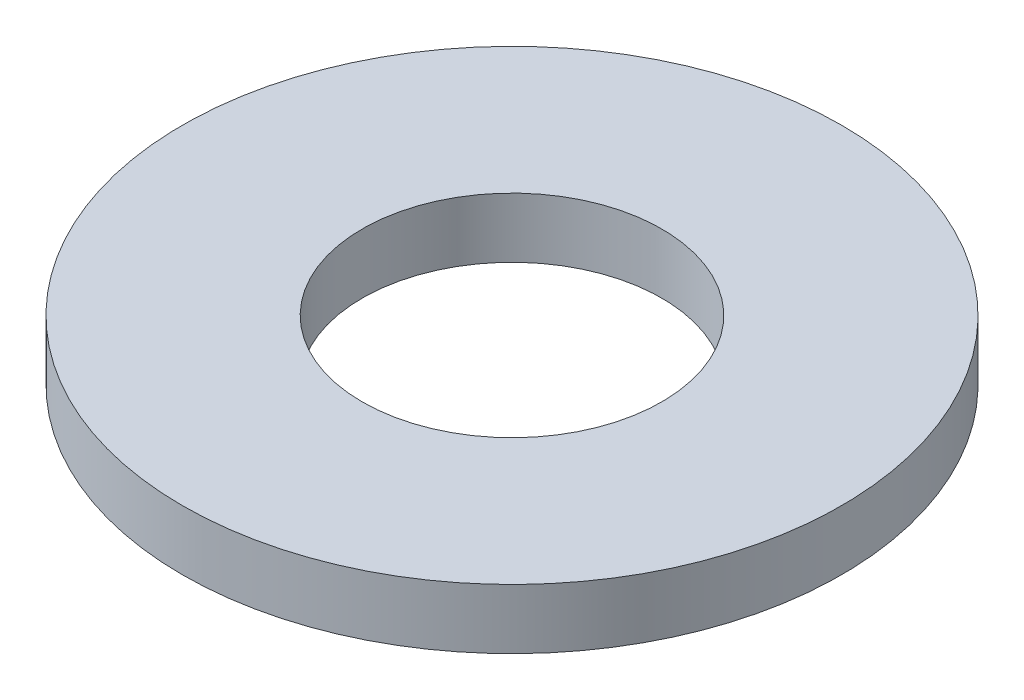
SolidWorks part; units mm, degrees
ref_plane "Front Plane" through (0, 0, 0) normal (0, 0, 1) x (1, 0, 0)
ref_plane "Top Plane" through (0, 0, 0) normal (0, 1, 0) x (1, 0, 0)
ref_plane "Right Plane" through (0, 0, 0) normal (1, 0, 0) x (0, 0, -1)
sketch "Sketch1" plane through (0, 0, 0) normal (0, 1, 0) x (1, 0, 0)
  circle A0 centre (0, 0) radius 1.25
  circle A1 centre (0, 0) radius 2.75
  dimension "D1" = 2.5
  dimension "D2" = 5.5
extrude "Boss-Extrude1" add sketch "Sketch1" along normal blind 0.5
